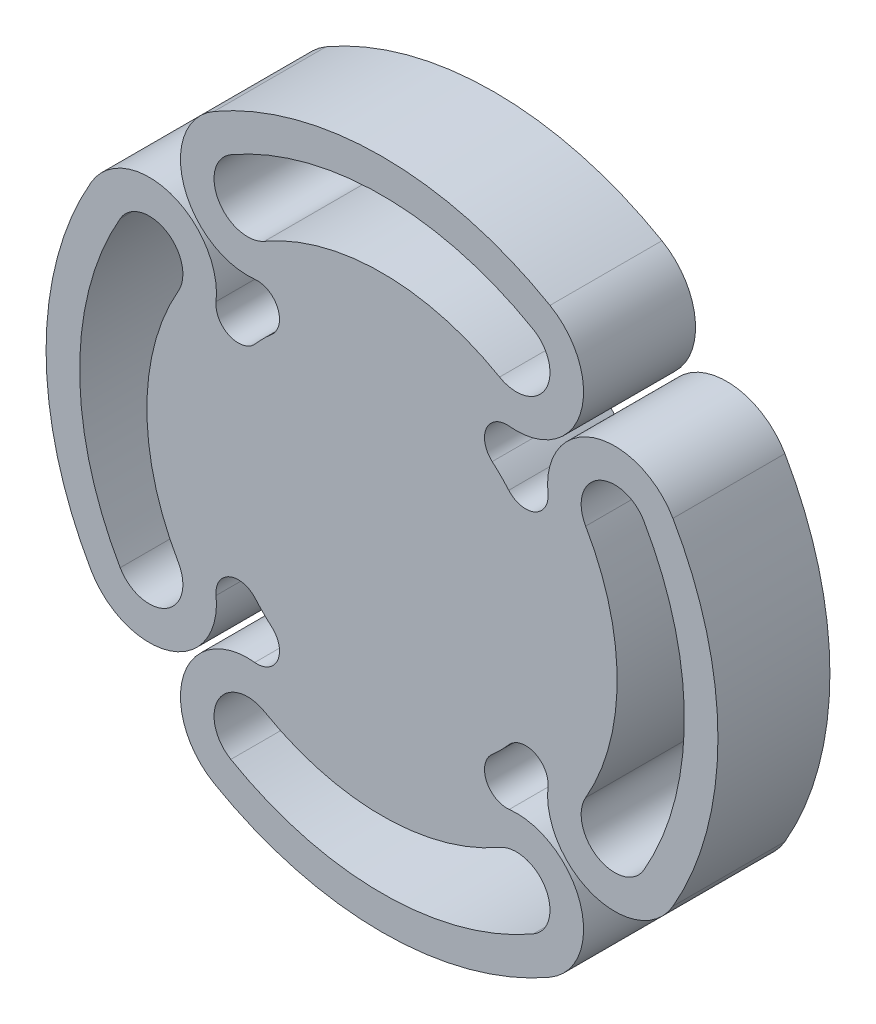
SolidWorks part; units mm, degrees
ref_plane "Front Plane" through (0, 0, 0) normal (0, 0, 1) x (1, 0, 0)
ref_plane "Top Plane" through (0, 0, 0) normal (0, 1, 0) x (1, 0, 0)
ref_plane "Right Plane" through (0, 0, 0) normal (1, 0, 0) x (0, 0, -1)
sketch "Sketch1" plane through (0, 0, 0) normal (0, 0, 1) x (1, 0, 0)
  line L0 (0, 0) -> (0, 39.6804) construction
  line L1 (19.737, 0) -> (-49980.263, 0) construction
  line L2 (0, -11.5295) -> (0, -50011.5295) construction
  arc A0 (-9.8415, 11.3202) -> (-11.3202, 9.8415) centre (0, 0) ccw
  circle A1 centre (0, 0) radius 24 construction
  arc A2 (-12, 20.7846) -> (12, 20.7846) centre (0, 0) cw construction
  arc A3 (15, 25.9808) -> (-15, 25.9808) centre (0, 0) ccw
  arc A5 (11.3652, 14.8183) -> (15, 25.9808) centre (12, 20.7846) ccw
  arc A6 (-15, 25.9808) -> (-11.3652, 14.8183) centre (-12, 20.7846) ccw
  arc A7 (-12, 20.7846) -> (12, 20.7846) centre (0, 0) cw construction
  arc A8 (13.5, 23.3827) -> (-13.5, 23.3827) centre (0, 0) ccw
  arc A9 (10.5, 18.1865) -> (-10.5, 18.1865) centre (0, 0) ccw
  arc A10 (10.5, 18.1865) -> (13.5, 23.3827) centre (12, 20.7846) ccw
  arc A11 (-13.5, 23.3827) -> (-10.5, 18.1865) centre (-12, 20.7846) ccw
  arc A12 (20.7846, 12) -> (20.7846, -12) centre (0, 0) cw construction
  arc A13 (25.9808, -15) -> (25.9808, 15) centre (0, 0) ccw
  arc A15 (14.8183, -11.3652) -> (25.9808, -15) centre (20.7846, -12) ccw
  arc A16 (25.9808, 15) -> (14.8183, 11.3652) centre (20.7846, 12) ccw
  arc A17 (20.7846, 12) -> (20.7846, -12) centre (0, 0) cw construction
  arc A18 (23.3827, -13.5) -> (23.3827, 13.5) centre (0, 0) ccw
  arc A19 (18.1865, -10.5) -> (18.1865, 10.5) centre (0, 0) ccw
  arc A20 (18.1865, -10.5) -> (23.3827, -13.5) centre (20.7846, -12) ccw
  arc A21 (23.3827, 13.5) -> (18.1865, 10.5) centre (20.7846, 12) ccw
  arc A22 (12, -20.7846) -> (-12, -20.7846) centre (0, 0) cw construction
  arc A23 (-15, -25.9808) -> (15, -25.9808) centre (0, 0) ccw
  arc A25 (-11.3652, -14.8183) -> (-15, -25.9808) centre (-12, -20.7846) ccw
  arc A26 (15, -25.9808) -> (11.3652, -14.8183) centre (12, -20.7846) ccw
  arc A27 (12, -20.7846) -> (-12, -20.7846) centre (0, 0) cw construction
  arc A28 (-13.5, -23.3827) -> (13.5, -23.3827) centre (0, 0) ccw
  arc A29 (-10.5, -18.1865) -> (10.5, -18.1865) centre (0, 0) ccw
  arc A30 (-10.5, -18.1865) -> (-13.5, -23.3827) centre (-12, -20.7846) ccw
  arc A31 (13.5, -23.3827) -> (10.5, -18.1865) centre (12, -20.7846) ccw
  arc A32 (-20.7846, -12) -> (-20.7846, 12) centre (0, 0) cw construction
  arc A33 (-25.9808, 15) -> (-25.9808, -15) centre (0, 0) ccw
  arc A35 (-14.8183, 11.3652) -> (-25.9808, 15) centre (-20.7846, 12) ccw
  arc A36 (-25.9808, -15) -> (-14.8183, -11.3652) centre (-20.7846, -12) ccw
  arc A37 (-20.7846, -12) -> (-20.7846, 12) centre (0, 0) cw construction
  arc A38 (-23.3827, 13.5) -> (-23.3827, -13.5) centre (0, 0) ccw
  arc A39 (-18.1865, 10.5) -> (-18.1865, -10.5) centre (0, 0) ccw
  arc A40 (-18.1865, 10.5) -> (-23.3827, 13.5) centre (-20.7846, 12) ccw
  arc A41 (-23.3827, -13.5) -> (-18.1865, -10.5) centre (-20.7846, -12) ccw
  arc A42 (-9.8415, 11.3202) -> (-11.3652, 14.8183) centre (-11.1536, 12.8295) ccw
  arc A43 (9.8415, 11.3202) -> (11.3652, 14.8183) centre (11.1536, 12.8295) cw
  arc A44 (11.3202, -9.8415) -> (14.8183, -11.3652) centre (12.8295, -11.1536) cw
  arc A45 (11.3202, 9.8415) -> (14.8183, 11.3652) centre (12.8295, 11.1536) ccw
  arc A46 (-9.8415, -11.3202) -> (-11.3652, -14.8183) centre (-11.1536, -12.8295) cw
  arc A47 (9.8415, -11.3202) -> (11.3652, -14.8183) centre (11.1536, -12.8295) ccw
  arc A48 (-11.3202, 9.8415) -> (-14.8183, 11.3652) centre (-12.8295, 11.1536) cw
  arc A49 (-11.3202, -9.8415) -> (-14.8183, -11.3652) centre (-12.8295, -11.1536) ccw
  arc A50 (-11.3202, -9.8415) -> (-9.8415, -11.3202) centre (0, 0) ccw
  arc A51 (11.3202, 9.8415) -> (9.8415, 11.3202) centre (0, 0) ccw
  arc A52 (9.8415, -11.3202) -> (11.3202, -9.8415) centre (0, 0) ccw
  point P6 (0, 24)
  point P11 (0, 24)
  point P26 (24, 0)
  point P31 (24, 0)
  point P40 (0, -24)
  point P45 (0, -24)
  point P54 (-24, 0)
  point P59 (-24, 0)
  point P66 (0, 0)
  point P91 (0, 0)
  dimension "D1" = 30
  dimension "D2" = 48
  dimension "D3" = 60
  dimension "D4" = 6
  dimension "D7" = 2
  dimension "D9" = 30
  dimension "D10" = 6
  dimension "D11" = 6
  dimension "D12" = 6
  dimension "D5" = 6
  dimension "D6" = 4
  dimension "D8" = 4
extrude "Boss-Extrude1" add sketch "Sketch1" along normal mid plane 10
